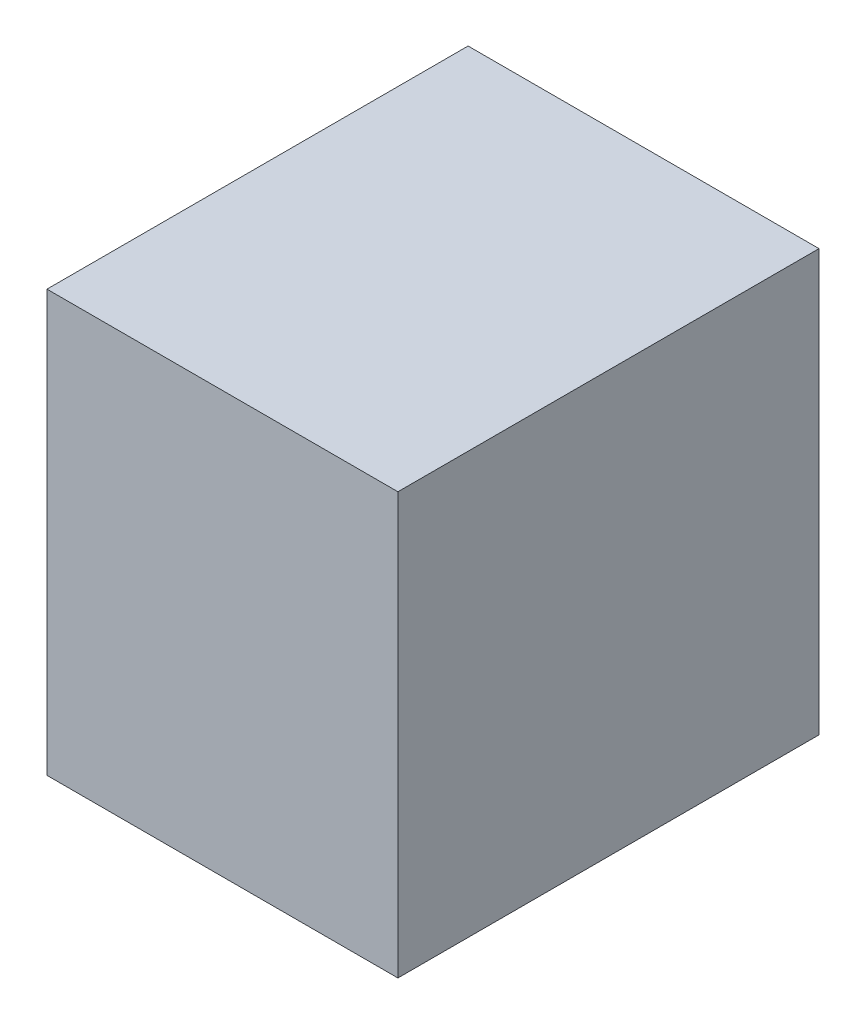
SolidWorks part; units mm, degrees
ref_plane "Front Plane" through (0, 0, 0) normal (0, 0, 1) x (1, 0, 0)
ref_plane "Top Plane" through (0, 0, 0) normal (0, 1, 0) x (1, 0, 0)
ref_plane "Right Plane" through (0, 0, 0) normal (1, 0, 0) x (0, 0, -1)
other "Configuration Table"
sketch "Sketch1" plane through (0, 0, 0) normal (0, 0, 1) x (1, 0, 0)
  line L1 (525, 640) -> (575, 640)
  line L2 (525, 640) -> (525, 700)
  line L3 (525, 700) -> (575, 700)
  line L4 (575, 640) -> (575, 700)
extrude "PACK_flap_servo_25kgcm_3_1" add sketch "Sketch1" against normal blind 60 from offset 170 separate body
